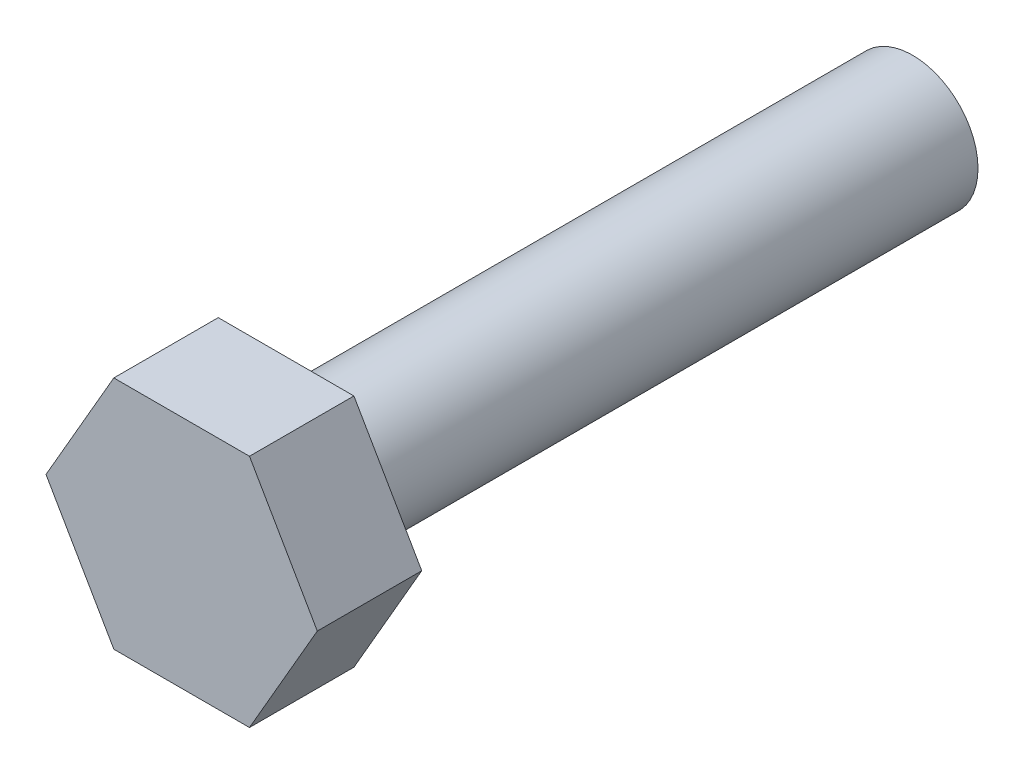
SolidWorks part; units mm, degrees
ref_plane "Plan de face" through (0, 0, 0) normal (0, 0, 1) x (1, 0, 0)
ref_plane "Plan de dessus" through (0, 0, 0) normal (0, 1, 0) x (1, 0, 0)
ref_plane "Plan de droite" through (0, 0, 0) normal (1, 0, 0) x (0, 0, -1)
sketch "Esquisse1" plane through (0, 0, 0) normal (0, 0, 1) x (1, 0, 0)
  circle A0 centre (0, 0) radius 3.9751
  dimension "D1" = 7.9502
extrude "Boss.-Extru.1" add sketch "Esquisse1" against normal blind 38.1
sketch "Esquisse2" plane through (0, 0, 0) normal (0, 0, 1) x (1, 0, 0)
  line L0 (4.3726, 0) -> (-4.3726, 0) construction
  line L1 (8.2489, 0) -> (4.1244, 7.1437)
  line L2 (4.1244, 7.1437) -> (-4.1244, 7.1437)
  line L3 (-4.1244, 7.1437) -> (-8.2489, 0)
  line L4 (-8.2489, 0) -> (-4.1244, -7.1438)
  line L5 (-4.1244, -7.1438) -> (4.1244, -7.1438)
  line L6 (4.1244, -7.1438) -> (8.2489, 0)
  circle A0 centre (0, 0) radius 7.1438 construction
  dimension "D1" = 14.2875
extrude "Boss.-Extru.2" add sketch "Esquisse2" along normal blind 6.35
